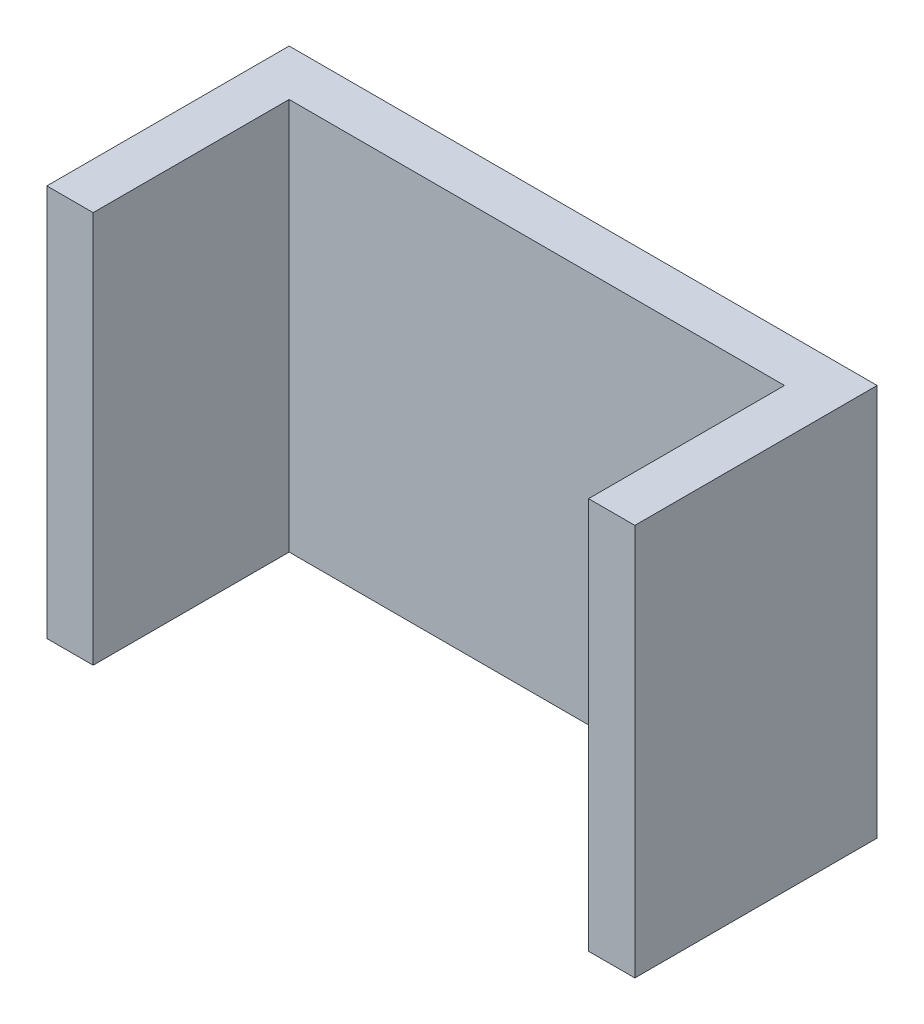
SolidWorks part; units mm, degrees
ref_plane "Front Plane" through (0, 0, 0) normal (0, 0, 1) x (1, 0, 0)
ref_plane "Top Plane" through (0, 0, 0) normal (0, 1, 0) x (1, 0, 0)
ref_plane "Right Plane" through (0, 0, 0) normal (1, 0, 0) x (0, 0, -1)
sketch "Sketch3" plane through (0, 0, 0) normal (0, 1, 0) x (1, 0, 0)
  line L0 (0, -3) -> (0, 3) construction
  line L1 (-38.1, -3) -> (38.1, -3)
  line L2 (-38.1, -3) -> (-38.1, 3)
  line L3 (-38.1, 3) -> (38.1, 3)
  line L4 (38.1, -3) -> (38.1, 3)
  line L5 (-38.1, -3) -> (38.1, 3) construction
  line L6 (-38.1, 3) -> (38.1, -3) construction
  line L7 (-38.1, -3) -> (-32.1, -3)
  line L8 (-38.1, -3) -> (-38.1, -28.4)
  line L9 (-38.1, -28.4) -> (-32.1, -28.4)
  line L10 (-32.1, -3) -> (-32.1, -28.4)
  line L11 (38.1, -28.4) -> (32.1, -28.4)
  line L12 (32.1, -3) -> (32.1, -28.4)
  line L13 (38.1, -3) -> (32.1, -3)
  line L14 (38.1, -3) -> (38.1, -28.4)
  point P0 (0, 0)
  dimension "D1" = 76.2
  dimension "D2" = 6
  dimension "D3" = 25.4
  dimension "D4" = 6
extrude "Boss-Extrude1" add sketch "Sketch3" along normal blind 50.8 contours L10 L1 L8 L9 | L1 L4 L3 L2 | L14 L1 L12 L11
